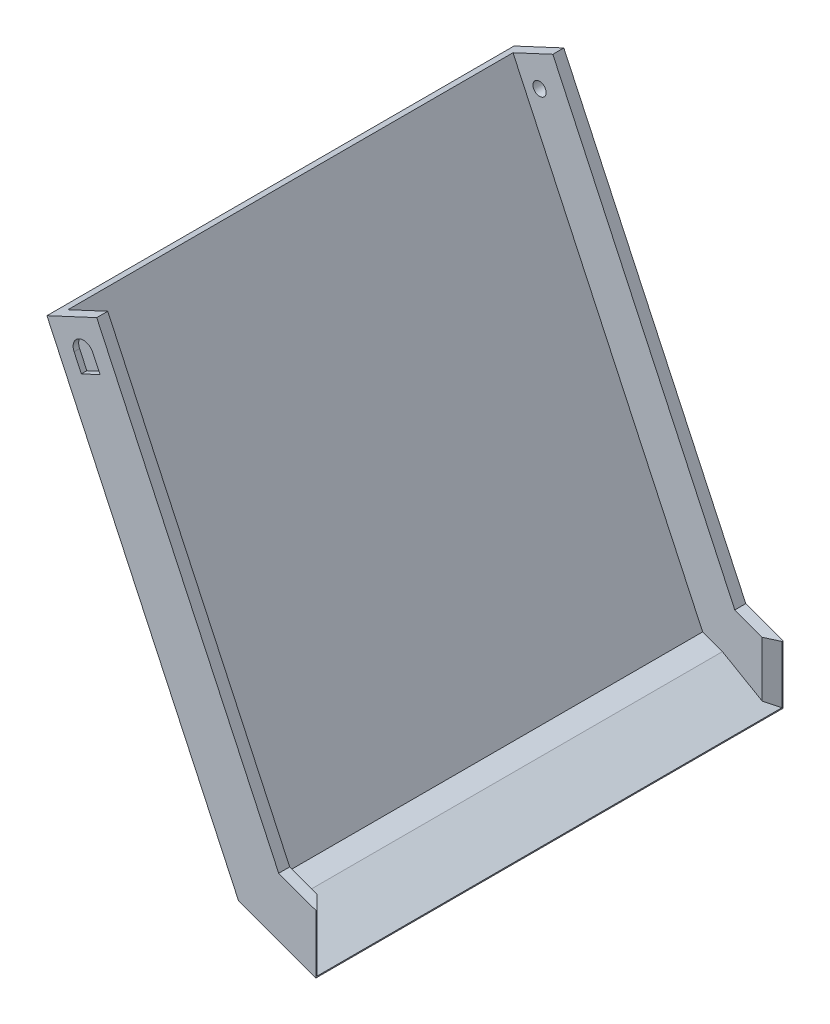
SolidWorks part; units mm, degrees
other "标注1"
sketch "草图5" plane through (-80.0481, -20.7055, 170) normal (0, 0, 1) x (1, 0, 0)
ref_plane "前视基准面" through (0, 0, 0) normal (0, 0, 1) x (1, 0, 0)
ref_plane "上视基准面" through (0, 0, 0) normal (0, 1, 0) x (1, 0, 0)
ref_plane "右视基准面" through (0, 0, 0) normal (1, 0, 0) x (0, 0, -1)
other "Configuration Table"
sketch "草图1" plane through (0, 0, 0) normal (0, 0, 1) x (1, 0, 0)
  line L0 (0, 0) -> (0, -21.2836)
  line L1 (0, -21.2836) -> (-28.1908, -11.023)
  line L2 (-28.1908, -11.023) -> (-97.9228, 138.5178)
  line L3 (-97.9228, 138.5178) -> (-79.7966, 146.9702)
  line L4 (-79.7966, 146.9702) -> (-13.5657, 4.9375)
  line L5 (-13.5657, 4.9375) -> (0, 0)
  dimension "D1" = 20
  dimension "D2" = 20
  dimension "D3" = 135
  dimension "D4" = 165
  dimension "D5" = 30
  dimension "D6" = 70
extrude "凸台-拉伸1" add sketch "草图1" along normal blind 170 contours L4 L5 L0 L1 L2 L3
shell "抽壳7" thickness 4
sketch "草图2" plane through (0, 0, 4) normal (0, 0, 1) x (1, 0, 0)
  line L0 (0, 0) -> (0, -21.2836) construction
  line L1 (0, -20.8836) -> (-19.5292, -9.6084)
  line L2 (-19.5292, -9.6084) -> (0, -9.6084)
  line L3 (0, -9.6084) -> (0, -20.8836)
  line L4 (0, -21.2836) -> (-28.1908, -11.023) construction
  point P7 (0, 0)
  point P9 (0, -19.7419)
  dimension "D1" = 10
  dimension "D2" = 0.4
sketch "草图4" plane through (0, 0, 170) normal (0, 0, 1) x (1, 0, 0)
  line L0 (-97.9228, 138.5178) -> (-79.7966, 146.9702) construction
  line L1 (-81.2349, 135.2658) -> (-78.5935, 129.6013)
  line L2 (-88.8597, 142.744) -> (-75.3125, 113.6918) construction
  line L3 (-78.5935, 129.6013) -> (-85.3908, 126.4317)
  line L4 (-85.3908, 126.4317) -> (-88.0322, 132.0961)
  line L5 (-28.1908, -11.023) -> (-97.9228, 138.5178) construction
  line L6 (-79.7966, 146.9702) -> (-13.5657, 4.9375) construction
  arc A0 (-81.2349, 135.2658) -> (-88.0322, 132.0961) centre (-84.6335, 133.6809) ccw
  point P4 (-88.8597, 142.744)
  point P5 (-100.1553, 115.8297)
  point P6 (-104.9398, 124.557)
  dimension "D2" = 7.5
  dimension "D1" = 10
  dimension "D3" = 6.25
extrude "切除-拉伸2" cut sketch "草图4" against normal blind 2 contours L3 L4 A0 L1
extrude "切除-拉伸4" cut sketch "草图2" along direction (0, 0, -1) on the side of the normal up to surface (162 mm away)
chamfer "倒角2" distance 3.6 angle 45 2 edges at (0, -10.4418, 166) (0, -10.4418, 4)
sketch "草图7" plane through (0, 0, 0) normal (0, 0, -1) x (-1, 0, 0)
  line L0 (97.9228, 138.5178) -> (79.7966, 146.9702) construction
  line L1 (84.6335, 133.6809) -> (88.8597, 142.744) construction
  circle A0 centre (84.6335, 133.6809) radius 2.4
  point P4 (88.8597, 142.744)
  dimension "D2" = 4.8
  dimension "D1" = 10
extrude "切除-拉伸5" cut sketch "草图7" against normal blind 10 contours A0
